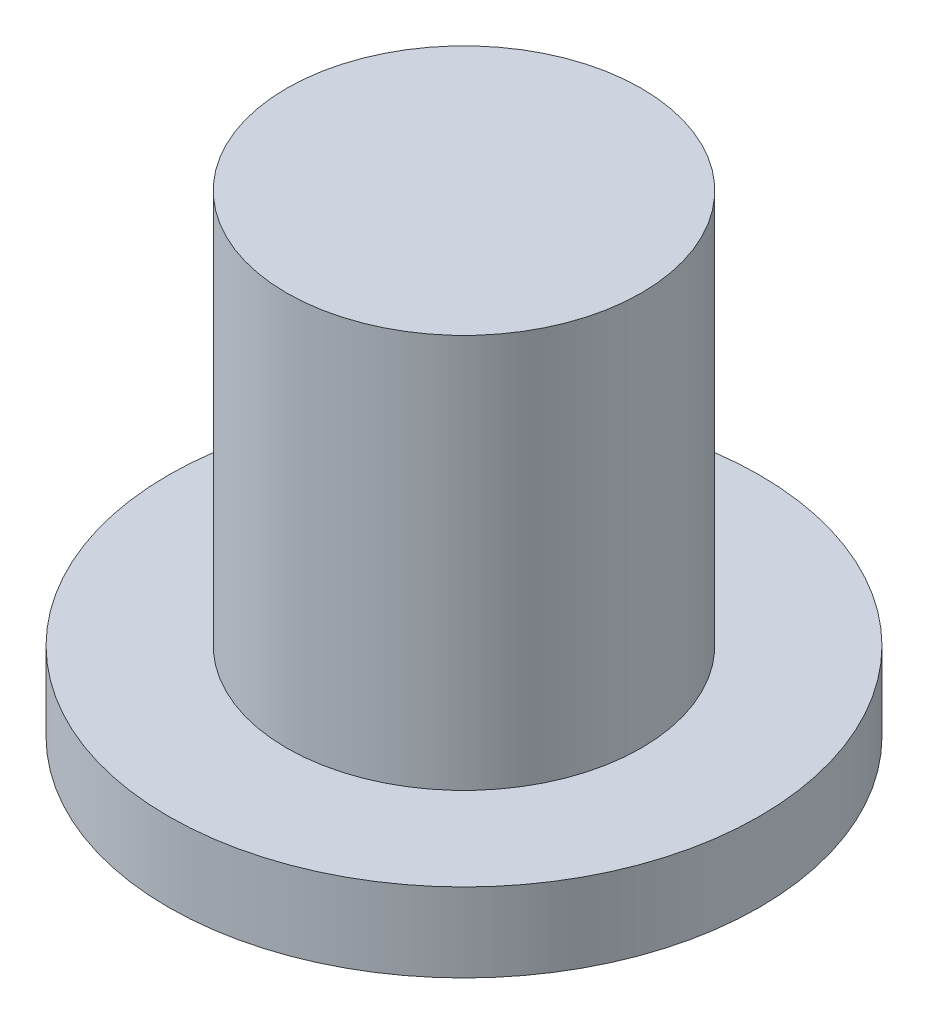
SolidWorks part; units mm, degrees
ref_plane "Front Plane" through (0, 0, 0) normal (0, 0, 1) x (1, 0, 0)
ref_plane "Top Plane" through (0, 0, 0) normal (0, 1, 0) x (1, 0, 0)
ref_plane "Right Plane" through (0, 0, 0) normal (1, 0, 0) x (0, 0, -1)
sketch "Sketch1" plane through (0, 0, 0) normal (0, 1, 0) x (1, 0, 0)
  circle A0 centre (0, 0) radius 1.905
  dimension "D1" = 3.81
extrude "Boss-Extrude1" add sketch "Sketch1" along normal blind 0.508
sketch "Sketch2" plane through (0, 0.508, 0) normal (0, 1, 0) x (1, 0, 0)
  circle A0 centre (0, 0) radius 1.143
  dimension "D1" = 2.286
extrude "Boss-Extrude2" add sketch "Sketch2" along normal blind 2.54
